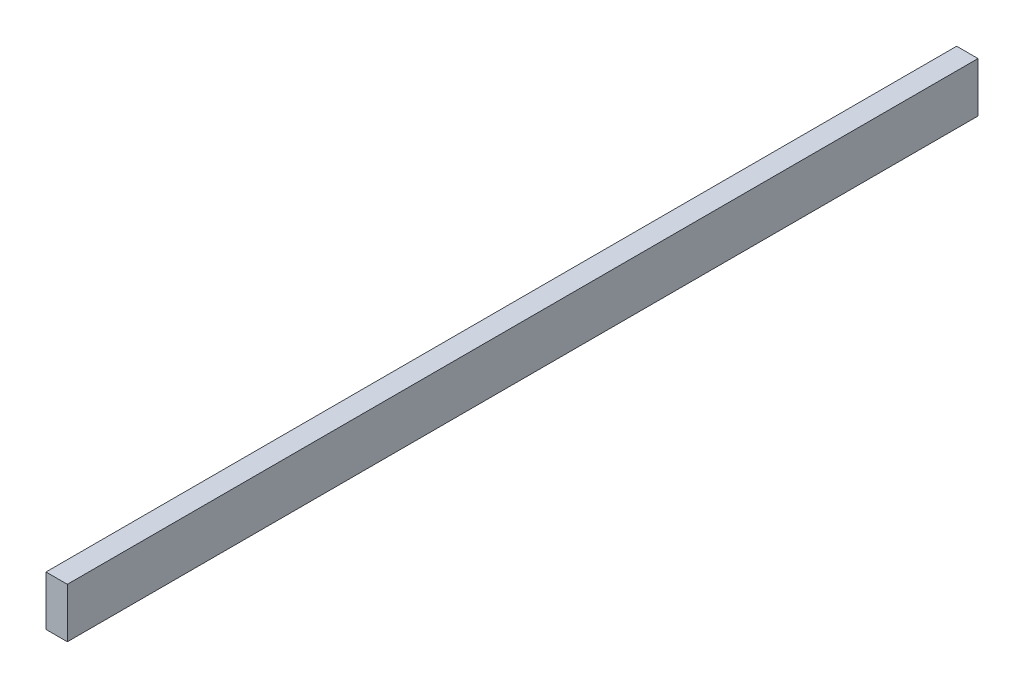
SolidWorks part; units mm, degrees
ref_plane "Front Plane" through (0, 0, 0) normal (0, 0, 1) x (1, 0, 0)
ref_plane "Top Plane" through (0, 0, 0) normal (0, 1, 0) x (1, 0, 0)
ref_plane "Right Plane" through (0, 0, 0) normal (1, 0, 0) x (0, 0, -1)
sketch "Sketch1" plane through (0, 0, 0) normal (1, 0, 0) x (0, 0, -1)
  line L1 (-812.8, -44.45) -> (812.8, -44.45)
  line L2 (-812.8, -44.45) -> (-812.8, 44.45)
  line L3 (-812.8, 44.45) -> (812.8, 44.45)
  line L4 (812.8, -44.45) -> (812.8, 44.45)
  line L5 (-812.8, -44.45) -> (812.8, 44.45) construction
  line L6 (-812.8, 44.45) -> (812.8, -44.45) construction
  point P0 (0, 0)
  dimension "D1" = 88.9
  dimension "D2" = 1625.6
extrude "Boss-Extrude1" add sketch "Sketch1" along normal blind 38.1
